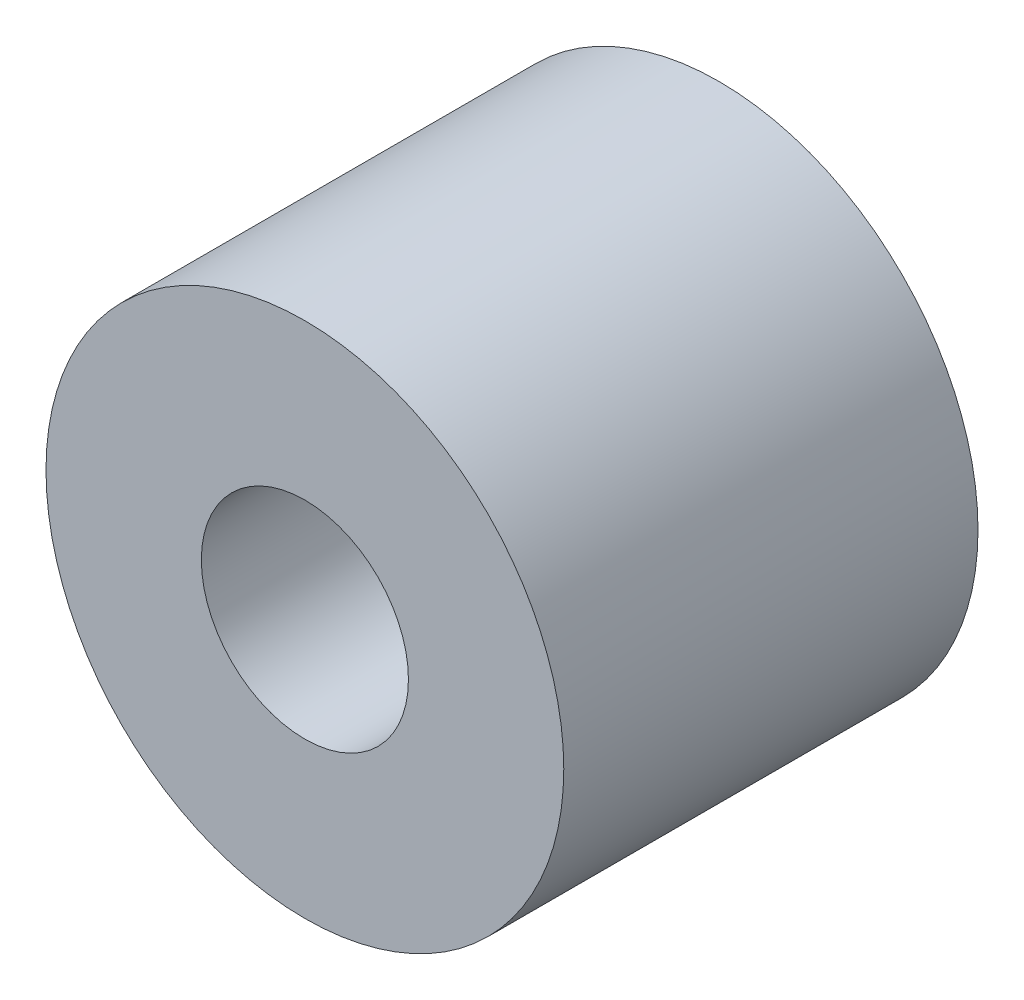
SolidWorks part; units mm, degrees
ref_plane "Front Plane" through (0, 0, 0) normal (0, 0, 1) x (1, 0, 0)
ref_plane "Top Plane" through (0, 0, 0) normal (0, 1, 0) x (1, 0, 0)
ref_plane "Right Plane" through (0, 0, 0) normal (1, 0, 0) x (0, 0, -1)
sketch "Sketch1" plane through (0, 0, 0) normal (0, 0, 1) x (1, 0, 0)
  circle A0 centre (0, 0) radius 25
  dimension "D1" = 50
extrude "Boss-Extrude1" add sketch "Sketch1" along normal blind 40 contours A0
sketch "Sketch2" plane through (0, 0, 40) normal (0, 0, 1) x (1, 0, 0)
  circle A0 centre (0, 0) radius 10
  dimension "D1" = 20
extrude "Cut-Extrude1" cut sketch "Sketch2" against normal blind 30 contours A0
